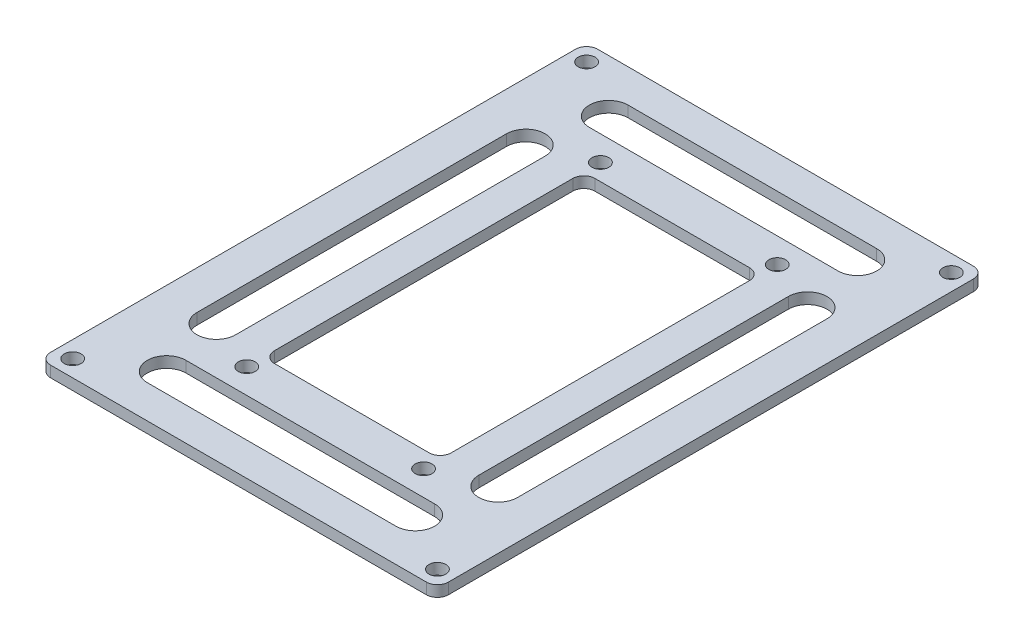
SolidWorks part; units mm, degrees
material "环氧玻璃布层压板"
ref_plane "前视基准面" through (0, 0, 0) normal (0, 0, 1) x (1, 0, 0)
ref_plane "上视基准面" through (0, 0, 0) normal (0, 1, 0) x (1, 0, 0)
ref_plane "右视基准面" through (0, 0, 0) normal (1, 0, 0) x (0, 0, -1)
sketch "草图1" plane through (0, 0, 0) normal (0, 1, 0) x (1, 0, 0)
  line L1 (-36, -49.5) -> (36, -49.5)
  line L2 (-36, -49.5) -> (-36, 49.5)
  line L3 (-36, 49.5) -> (36, 49.5)
  line L4 (36, -49.5) -> (36, 49.5)
  line L5 (0, 49.5) -> (0, -49.5) construction
  line L6 (-36, 0) -> (36, 0) construction
  point P0 (0, 0)
  dimension "D1" = 72
  dimension "D2" = 99
extrude "凸台-拉伸1" add sketch "草图1" along normal blind 2
sketch "草图3" plane through (0, 2, 0) normal (0, 1, 0) x (1, 0, 0)
  line L8 (33, -46.5) -> (33, 46.5)
  line L9 (33, 46.5) -> (-33, 46.5)
  line L10 (-33, 46.5) -> (-33, -46.5)
  line L11 (-33, -46.5) -> (33, -46.5)
  line L12 (33, -46.5) -> (33, 46.5) construction
  line L13 (33, 46.5) -> (-33, 46.5) construction
  line L14 (-33, 46.5) -> (-33, -46.5) construction
  line L15 (-33, -46.5) -> (33, -46.5) construction
  circle A0 centre (33, 46.5) radius 1.525
  circle A1 centre (-33, 46.5) radius 1.525
  circle A2 centre (-33, -46.5) radius 1.525
  circle A3 centre (33, -46.5) radius 1.525
  dimension "D2" = 3.05
  dimension "D1" = 3
extrude "切除-拉伸1" cut sketch "草图3" against normal blind 2
sketch "草图4" plane through (0, 2, 0) normal (0, 1, 0) x (1, 0, 0)
  line L1 (-16, -32) -> (16, -32) construction
  line L2 (-16, -32) -> (-16, 32) construction
  line L3 (-16, 32) -> (16, 32) construction
  line L4 (16, -32) -> (16, 32) construction
  line L5 (0, 32) -> (0, -32) construction
  line L6 (-16, 0) -> (16, 0) construction
  circle A0 centre (16, -32) radius 1.525
  circle A1 centre (-16, -32) radius 1.525
  circle A2 centre (-16, 32) radius 1.525
  circle A3 centre (16, 32) radius 1.525
  point P0 (0, 0)
  dimension "D3" = 3.05
  dimension "D1" = 32
  dimension "D2" = 64
extrude "切除-拉伸2" cut sketch "草图4" against normal blind 2
sketch "草图5" plane through (0, 2, 0) normal (0, 1, 0) x (1, 0, 0)
  line L1 (-16, -29) -> (16, -29)
  line L2 (-16, -29) -> (-16, 29)
  line L3 (-16, 29) -> (16, 29)
  line L4 (16, -29) -> (16, 29)
  line L5 (0, 29) -> (0, -29) construction
  line L6 (-16, 0) -> (16, 0) construction
  circle A0 centre (16, 32) radius 1.525 construction
  point P0 (0, 0)
  dimension "D1" = 3
  dimension "D2" = 32
extrude "切除-拉伸3" cut sketch "草图5" against normal blind 2
fillet "圆角1" radius 2 4 edges at (-16, 1, -29) (16, 1, -29) (-16, 1, 29) (16, 1, 29)
sketch "草图6" plane through (0, 2, 0) normal (0, 1, 0) x (1, 0, 0)
  line L0 (25.5, -28) -> (25.5, 28) construction
  line L1 (22, -28) -> (22, 28)
  line L2 (29, -28) -> (29, 28)
  line L3 (16, -27) -> (16, 27) construction
  line L4 (36, -49.5) -> (36, 49.5) construction
  line L5 (0, 0) -> (25.5, 0) construction
  line L6 (0, 0) -> (0, 29) construction
  line L7 (14, 29) -> (-14, 29) construction
  line L8 (-25.5, -28) -> (-25.5, 28) construction
  line L9 (-22, -28) -> (-22, 28)
  line L10 (-29, -28) -> (-29, 28)
  line L11 (-22.5, 40) -> (22.5, 40) construction
  line L12 (-22.5, 43.5) -> (22.5, 43.5)
  line L13 (-22.5, 36.5) -> (22.5, 36.5)
  line L14 (0, 40) -> (0, 29) construction
  line L15 (36, 49.5) -> (-36, 49.5) construction
  line L16 (-22.5, -40) -> (22.5, -40) construction
  line L17 (-22.5, -43.5) -> (22.5, -43.5)
  line L18 (-22.5, -36.5) -> (22.5, -36.5)
  arc A0 (22, -28) -> (29, -28) centre (25.5, -28) ccw
  arc A1 (29, 28) -> (22, 28) centre (25.5, 28) ccw
  arc A2 (-22, -28) -> (-29, -28) centre (-25.5, -28) cw
  arc A3 (-29, 28) -> (-22, 28) centre (-25.5, 28) cw
  arc A4 (-22.5, 43.5) -> (-22.5, 36.5) centre (-22.5, 40) ccw
  arc A5 (22.5, 36.5) -> (22.5, 43.5) centre (22.5, 40) ccw
  arc A6 (-22.5, -43.5) -> (-22.5, -36.5) centre (-22.5, -40) cw
  arc A7 (22.5, -36.5) -> (22.5, -43.5) centre (22.5, -40) cw
  point P2 (25.5, 0)
  point P19 (-25.5, 0)
  point P26 (0, 40)
  point P36 (0, -40)
  dimension "D4" = 3.5
  dimension "D6" = 45
  dimension "D1" = 6
  dimension "D2" = 7
  dimension "D3" = 56
  dimension "D5" = 6
extrude "切除-拉伸4" cut sketch "草图6" against normal blind 2
fillet "圆角2" radius 2 4 edges at (-36, 1, -49.5) (36, 1, -49.5) (-36, 1, 49.5) (36, 1, 49.5)
